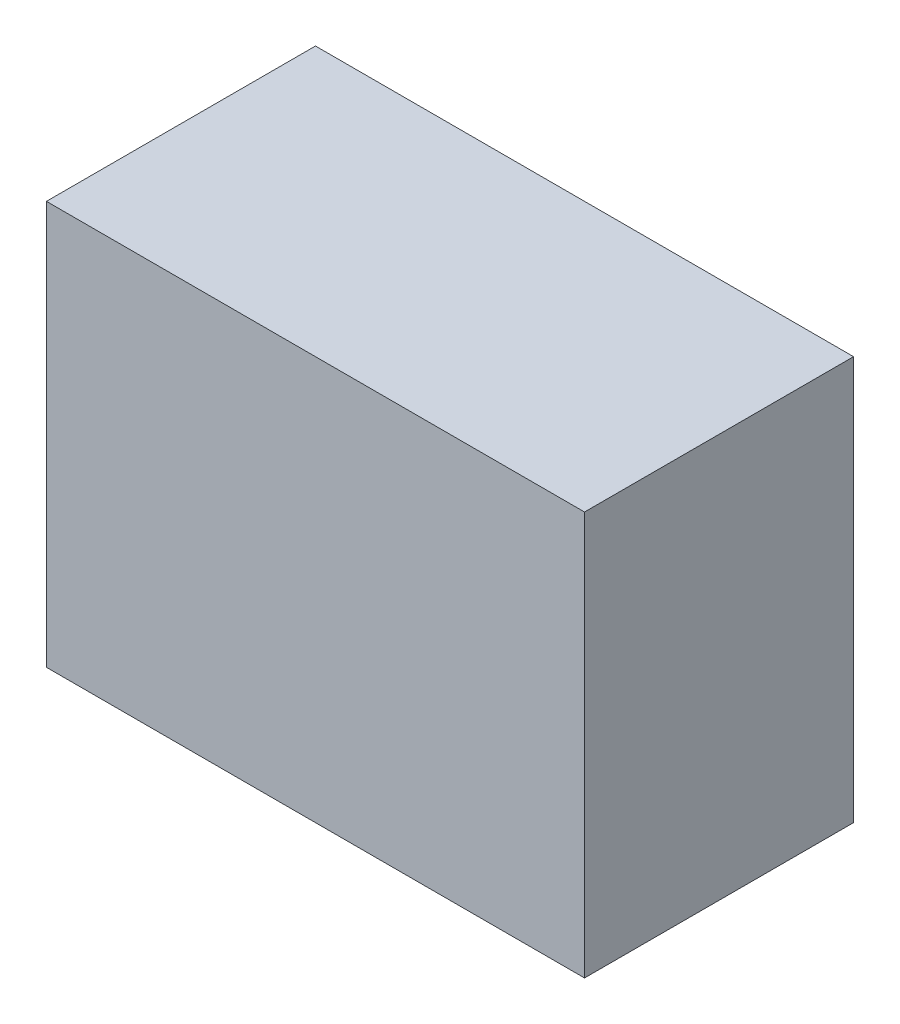
SolidWorks part; units mm, degrees
ref_plane "Front Plane" through (0, 0, 0) normal (0, 0, 1) x (1, 0, 0)
ref_plane "Top Plane" through (0, 0, 0) normal (0, 1, 0) x (1, 0, 0)
ref_plane "Right Plane" through (0, 0, 0) normal (1, 0, 0) x (0, 0, -1)
sketch "Sketch1" plane through (0, 0, 0) normal (0, 0, 1) x (1, 0, 0)
  line L0 (-20, -15) -> (20, -15)
  line L1 (20, -15) -> (20, 15)
  line L2 (20, 15) -> (-20, 15)
  line L3 (-20, 15) -> (-20, -15)
extrude "Boss-Extrude1" add sketch "Sketch1" along normal blind 20
